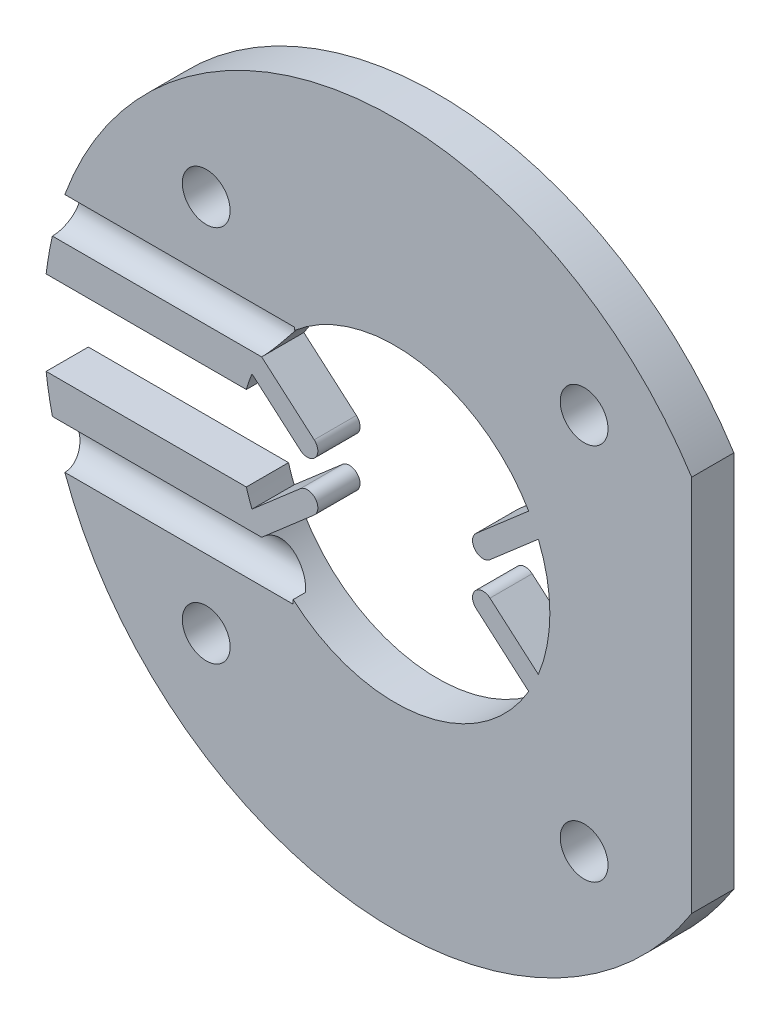
SolidWorks part; units mm, degrees
ref_plane "Plan de face" through (0, 0, 0) normal (0, 0, 1) x (1, 0, 0)
ref_plane "Plan de dessus" through (0, 0, 0) normal (0, 1, 0) x (1, 0, 0)
ref_plane "Plan de droite" through (0, 0, 0) normal (1, 0, 0) x (0, 0, -1)
sketch "Esquisse1" plane through (0, 0, 0) normal (0, 0, 1) x (1, 0, 0)
  circle A0 centre (0, 0) radius 25
  circle A1 centre (-13.435, 13.435) radius 1.7
  circle A2 centre (13.435, 13.435) radius 1.7
  circle A3 centre (13.435, -13.435) radius 1.7
  circle A4 centre (-13.435, -13.435) radius 1.7
  point P19 (0, 0)
  dimension "D1" = 50
  dimension "D5" = 19
  dimension "D6" = 3.4
  dimension "D4" = 4
extrude "Boss.-Extru.1" add sketch "Esquisse1" along normal blind 3
ref_plane "Plan1" through (0, 0, 0) normal (1, 0, 0) x (0, 0, -1)
sketch "Esquisse6" plane through (0, 0, 0) normal (0, 0, -1) x (-1, 0, 0)
  circle A0 centre (0, 0) radius 11
  dimension "D1" = 22
extrude "Enlèv. mat.-Extru.2" cut sketch "Esquisse6" against normal through all
sketch "Esquisse8" plane through (0, 0, 3) normal (0, 0, 1) x (1, 0, 0)
  line L0 (-6.5, 2) -> (6.5, 2) construction
  line L1 (6.5, 2) -> (6.5, -2) construction
  line L2 (6.5, -2) -> (-6.5, -2) construction
  line L3 (-6.5, 2) -> (-6.5, -2) construction
  line L4 (-6.25, 1.75) -> (-6.25, 2) construction
  line L5 (-6.25, 1.75) -> (-6.5, 1.75) construction
  line L6 (-6.25, -1.75) -> (-6.5, -1.75) construction
  line L7 (-6.25, -1.75) -> (-6.25, -2) construction
  line L8 (6.25, 1.75) -> (6.25, 2) construction
  line L9 (6.25, 1.75) -> (6.5, 1.75) construction
  line L10 (6.25, -1.75) -> (6.5, -1.75) construction
  line L11 (6.25, -1.75) -> (6.25, -2) construction
  line L12 (6.5, 0) -> (-6.5, 0) construction
  circle A0 centre (-6.25, 1.75) radius 0.25
  circle A1 centre (-6.25, -1.75) radius 0.25
  circle A2 centre (6.25, 1.75) radius 0.25
  circle A3 centre (6.25, -1.75) radius 0.25
sketch "Esquisse10" plane through (0, 0, 3) normal (0, 0, 1) x (1, 0, 0)
  line L0 (-10, 0) -> (10, 0) construction
  line L1 (10, 0) -> (10, 5) construction
  line L2 (10, 5) -> (-10, 5) construction
  line L3 (-10, 5) -> (-10, 0) construction
  line L4 (6.5, -2) -> (-6.5, -2) construction
  line L5 (-6.5, 2) -> (6.5, 2) construction
  line L6 (6.5, 2) -> (6.5, -2) construction
  line L7 (6.5, 0) -> (-6.5, 0) construction
  line L8 (9.2495, -0.5365) -> (9.2495, 3.4635) construction
  line L9 (10, 0) -> (10, -5) construction
  line L10 (10, -5) -> (-10, -5) construction
  line L11 (-10, -5) -> (-10, 0) construction
  line L12 (-6.25, -1.75) -> (-10, -5) construction
  line L13 (-5.7588, -2.3168) -> (-9.5088, -5.5668)
  line L14 (-6.7412, -1.1832) -> (-10.4912, -4.4332)
  line L15 (-6.25, 1.75) -> (-10, 5) construction
  line L16 (-6.7412, 1.1832) -> (-10.4912, 4.4332)
  line L17 (-5.7588, 2.3168) -> (-9.5088, 5.5668)
  line L18 (10, -5) -> (6.25, -1.75) construction
  line L19 (9.5088, -5.5668) -> (5.7588, -2.3168)
  line L20 (10.4912, -4.4332) -> (6.7412, -1.1832)
  line L21 (10, 5) -> (6.25, 1.75) construction
  line L22 (10.4912, 4.4332) -> (6.7412, 1.1832)
  line L23 (9.5088, 5.5668) -> (5.7588, 2.3168)
  arc A0 (-5.7588, -2.3168) -> (-6.7412, -1.1832) centre (-6.25, -1.75) ccw
  arc A1 (-10.4912, -4.4332) -> (-9.5088, -5.5668) centre (-10, -5) ccw
  arc A2 (-6.7412, 1.1832) -> (-5.7588, 2.3168) centre (-6.25, 1.75) ccw
  arc A3 (-9.5088, 5.5668) -> (-10.4912, 4.4332) centre (-10, 5) ccw
  arc A4 (9.5088, -5.5668) -> (10.4912, -4.4332) centre (10, -5) ccw
  arc A5 (6.7412, -1.1832) -> (5.7588, -2.3168) centre (6.25, -1.75) ccw
  arc A6 (10.4912, 4.4332) -> (9.5088, 5.5668) centre (10, 5) ccw
  arc A7 (5.7588, 2.3168) -> (6.7412, 1.1832) centre (6.25, 1.75) ccw
  point P12 (0, 0)
  point P18 (-8.125, -3.375)
  point P24 (-8.125, 3.375)
  point P31 (8.125, -3.375)
  point P38 (8.125, 3.375)
extrude "Boss.-Extru.6" add sketch "Esquisse10" against normal blind 3
sketch "Esquisse11" plane through (0, 0, 3) normal (0, 0, 1) x (1, 0, 0)
  line L1 (-10.0455, 3) -> (-28.6917, 3)
  line L2 (-10.0455, 3) -> (-10.0455, -3)
  line L3 (-10.0455, -3) -> (-28.6917, -3)
  line L4 (-28.6917, 3) -> (-28.6917, -3)
  line L6 (-10.0455, 0) -> (-28.6917, 0) construction
  line L7 (6.5, 0) -> (-6.5, 0) construction
extrude "Enlèv. mat.-Extru.3" cut sketch "Esquisse11" against normal through all
sketch "Esquisse12" plane through (0, 0, 3) normal (0, 0, 1) x (1, 0, 0)
  line L1 (-24.3751, -5.5545) -> (-7.2543, -5.5545)
  line L2 (-24.3751, -5.5545) -> (-24.3751, -7.0545)
  line L3 (-24.3751, -7.0545) -> (-7.2543, -7.0545)
  line L4 (-7.2543, -5.5545) -> (-7.2543, -7.0545)
  arc A0 (-24.8193, -3) -> (-24.8193, 3) centre (0, 0) ccw construction
revolve "Enlèvement de matière-Révolution1" cut sketch "Esquisse12" angle 360 about L3
sketch "Esquisse13" plane through (0, 0, 3) normal (0, 0, 1) x (1, 0, 0)
  line L1 (-24.3751, 5.5545) -> (-7.1629, 5.5545)
  line L2 (-24.3751, 5.5545) -> (-24.3751, 7.0545)
  line L3 (-24.3751, 7.0545) -> (-7.1629, 7.0545)
  line L4 (-7.1629, 5.5545) -> (-7.1629, 7.0545)
  arc A0 (-23.4909, -8.5545) -> (-24.8193, 3) centre (0, 0) ccw construction
revolve "Enlèvement de matière-Révolution2" cut sketch "Esquisse13" angle 360 about L3
sketch "Esquisse14" plane through (0, 0, 3) normal (0, 0, 1) x (1, 0, 0)
  line L1 (21.0832, -13.435) -> (27.5103, -13.435)
  line L2 (21.0832, -13.435) -> (21.0832, 15.7518)
  line L3 (21.0832, 15.7518) -> (27.5103, 15.7518)
  line L4 (27.5103, -13.435) -> (27.5103, 15.7518)
  arc A0 (-23.4909, -8.5545) -> (-23.4909, 8.5545) centre (0, 0) ccw construction
extrude "Enlèv. mat.-Extru.4" cut sketch "Esquisse14" against normal through all
equation "\"9.5.00mm\"=6"
